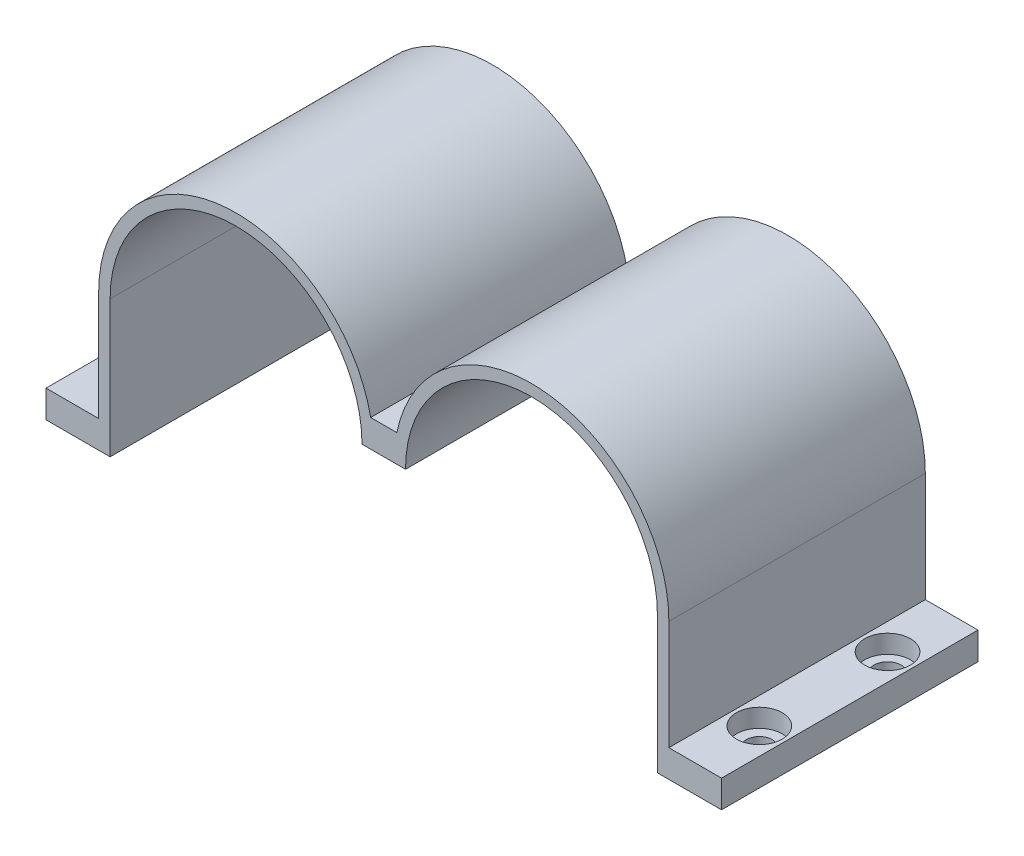
SolidWorks part; units mm, degrees
ref_plane "Alzado" through (0, 0, 0) normal (0, 0, 1) x (1, 0, 0)
ref_plane "Planta" through (0, 0, 0) normal (0, 1, 0) x (1, 0, 0)
ref_plane "Vista lateral" through (0, 0, 0) normal (1, 0, 0) x (0, 0, -1)
sketch "Croquis1" plane through (0, 0, 0) normal (0, 0, 1) x (1, 0, 0)
  line L0 (-2.375, 0) -> (2.375, 0)
  line L1 (-31.125, -11.9452) -> (-31.125, 0)
  line L6 (-29.875, 0) -> (-29.875, -14.9452)
  line L7 (0, 0) -> (0, -15) construction
  line L8 (-29.875, -14.9452) -> (-36.875, -14.9452)
  line L9 (-29.875, -14.9452) -> (-29.875, -9.9452)
  line L10 (-31.125, -11.9452) -> (-36.875, -11.9452)
  line L11 (-36.875, -14.9452) -> (-36.875, -11.9452)
  line L12 (31.125, -11.9452) -> (36.875, -11.9452)
  line L13 (36.875, -14.9452) -> (36.875, -11.9452)
  line L14 (29.875, -14.9452) -> (36.875, -14.9452)
  line L15 (29.875, -14.9452) -> (29.875, -9.9452)
  line L16 (29.875, 0) -> (29.875, -14.9452)
  line L17 (31.125, -11.9452) -> (31.125, 0)
  line L18 (-1.125, 0) -> (1.125, 0)
  line L19 (-1.4281, 3) -> (1.4281, 3)
  arc A1 (-2.375, 0) -> (-29.875, 0) centre (-16.125, 0) ccw
  arc A2 (29.875, 0) -> (2.375, 0) centre (16.125, 0) ccw
  arc A3 (-1.4281, 3) -> (-31.125, 0) centre (-16.125, 0) ccw
  arc A4 (31.125, 0) -> (1.4281, 3) centre (16.125, 0) ccw
  point P5 (0, 0)
  point P9 (-1.2157, 1.6468)
  dimension "D1" = 27.5
  dimension "D3" = 30
  dimension "D2" = 4.75
  dimension "D4" = 3
  dimension "D5" = 7
  dimension "D6" = 3
extrude "Saliente-Extruir1" add sketch "Croquis1" against normal blind 28 contours L17 A4 L19 A3 L1 L10 L11 L8 L6 A1 L0 L18 A2 L16 L15 L14 L13 L12
sketch "Croquis2" plane through (0, -11.9452, 0) normal (0, 1, 0) x (1, 0, 0)
  line L0 (-34, 28) -> (-34, 0) construction
  line L1 (-31.125, 28) -> (-36.875, 28) construction
  line L2 (-31.125, 0) -> (-36.875, 0) construction
  line L3 (0, 0) -> (0, 28) construction
  line L4 (-1.4281, 28) -> (1.4281, 28) construction
  circle A0 centre (-34, 21) radius 2.5
  circle A1 centre (-34, 7) radius 2.5
  circle A2 centre (-34, 21) radius 1.5
  circle A3 centre (-34, 7) radius 1.4079
  circle A4 centre (34, 7) radius 1.4079
  circle A5 centre (34, 7) radius 2.5
  circle A6 centre (34, 21) radius 1.5
  circle A7 centre (34, 21) radius 2.5
  dimension "D1" = 5
  dimension "D2" = 3
  dimension "D3" = 7
  dimension "D4" = 7
extrude "Cortar-Extruir1" cut sketch "Croquis2" against normal blind 2
sketch "Croquis3" plane through (0, -11.9452, 0) normal (0, 1, 0) x (1, 0, 0)
  circle A1 centre (-34, 7) radius 1.4079
  circle A2 centre (-34, 7) radius 1.4079
  circle A3 centre (-34, 21) radius 1.5
  circle A4 centre (-34, 21) radius 1.5
  dimension "D1" = 0
  dimension "D2" = 0
extrude "Cortar-Extruir2" cut sketch "Croquis3" against normal through all
sketch "Croquis4" plane through (0, -11.9452, 0) normal (0, 1, 0) x (1, 0, 0)
  circle A1 centre (34, 7) radius 1.4079
  circle A2 centre (34, 7) radius 1.4079
  circle A3 centre (34, 21) radius 1.5
  circle A4 centre (34, 21) radius 1.5
  dimension "D1" = 0
  dimension "D2" = 0
extrude "Cortar-Extruir3" cut sketch "Croquis4" against normal through all
